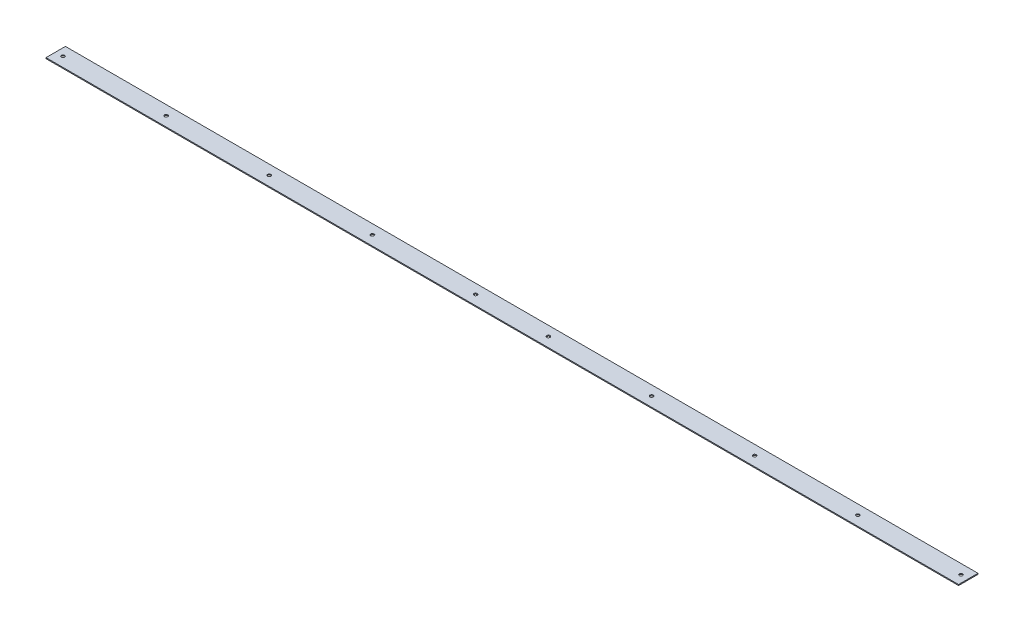
SolidWorks part; units mm, degrees
material "5052-H32"
ref_plane "Front Plane" through (0, 0, 0) normal (0, 0, 1) x (1, 0, 0)
ref_plane "Top Plane" through (0, 0, 0) normal (0, 1, 0) x (1, 0, 0)
ref_plane "Right Plane" through (0, 0, 0) normal (1, 0, 0) x (0, 0, -1)
sketch "Sketch1" plane through (0, 0, 0) normal (0, 1, 0) x (1, 0, 0)
  line L1 (940, -20) -> (-940, -20)
  line L2 (940, -20) -> (940, 20)
  line L3 (940, 20) -> (-940, 20)
  line L4 (-940, -20) -> (-940, 20)
  line L5 (940, -20) -> (-940, 20) construction
  line L6 (940, 20) -> (-940, -20) construction
  point P0 (0, 0)
  dimension "D1" = 40
  dimension "D2" = 1880
extrude "Boss-Extrude1" add sketch "Sketch1" along normal blind 2
sketch "Sketch2" plane through (0, 2, 0) normal (0, 1, 0) x (1, 0, 0)
  line L0 (-940, -20) -> (940, -20) construction
  line L1 (-940, 20) -> (-940, -20) construction
  line L2 (940, -20) -> (940, 20) construction
  circle A0 centre (-925, 0) radius 3.4
  circle A1 centre (-712.5, 0) radius 3.4
  circle A2 centre (-500, 0) radius 3.4
  circle A3 centre (-287.5, 0) radius 3.4
  circle A4 centre (-75, 0) radius 3.4
  circle A5 centre (925, 0) radius 3.4
  circle A6 centre (712.5, 0) radius 3.4
  circle A7 centre (500, 0) radius 3.4
  circle A8 centre (287.5, 0) radius 3.4
  circle A9 centre (75, 0) radius 3.4
  dimension "D1" = 6.8
  dimension "D5" = 212.5
  dimension "D8" = 5
  dimension "D2" = 20
  dimension "D3" = 15
  dimension "D6" = 15
  dimension "D7" = 20
  dimension "D9" = 212.5
  dimension "D4" = 5
extrude "Cut-Extrude1" cut sketch "Sketch2" against normal blind 10
